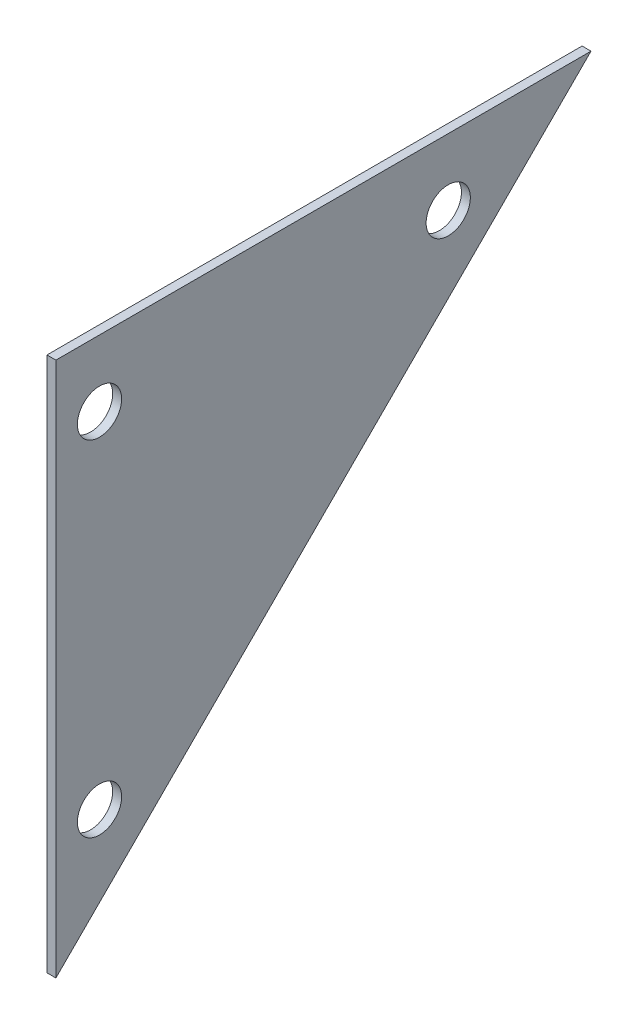
SolidWorks part; units mm, degrees
ref_plane "Front Plane" through (0, 0, 0) normal (0, 0, 1) x (1, 0, 0)
ref_plane "Top Plane" through (0, 0, 0) normal (0, 1, 0) x (1, 0, 0)
ref_plane "Right Plane" through (0, 0, 0) normal (1, 0, 0) x (0, 0, -1)
sketch "Sketch1" plane through (0, 0, 0) normal (1, 0, 0) x (0, 0, -1)
  line L0 (112.9407, 23.9242) -> (-39.4593, -128.4758)
  line L1 (-39.4593, 23.9242) -> (112.9407, 23.9242)
  line L2 (-39.4593, 23.9242) -> (-39.4593, -128.4758)
  dimension "D1" = 152.4
  dimension "D2" = 152.4
extrude "Boss-Extrude1" add sketch "Sketch1" along normal blind 2.54
sketch "Sketch2" plane through (2.54, 0, 0) normal (1, 0, 0) x (0, 0, -1)
  circle A0 centre (-27.0399, -93.1123) radius 9.525
  circle A1 centre (-27.0399, 5.0075) radius 9.525
  circle A2 centre (72.2765, 5.0075) radius 9.525
hole_wizard "CSK for M6 Flat Head Machine Screw1" positions "3DSketch1" profile "Sketch3" countersink size "M6" standard "ANSI Metric" end condition through all
sketch3d "3DSketch1"
  point P0 (2.54, 5.0075, 27.0399)
  point P3 (2.54, 5.0075, -72.2765)
  point P6 (2.54, -93.1123, 27.0399)
sketch "Sketch3" plane through (2.54, 5.0075, 27.0399) normal (0, 1, 0) x (0, 0, -1)
  line L0 (0, 0) -> (0, 2.54)
  line L1 (0, 2.54) -> (3.3, 2.54)
  line L2 (3.3, 2.54) -> (3.3, 28.4)
  line L3 (3.3, 28.4) -> (6.3, 25.4)
  line L4 (6.3, 25.4) -> (6.3, 0)
  line L6 (6.3, 0) -> (0, 0)
  line L7 (-3.3, 28.4) -> (-6.3, 25.4) construction
  line L11 (0, -6.35) -> (0, 107.95) construction
  dimension "Thru Hole Dia." = 6.6
  dimension "Thru Hole Depth" = 2.54
  dimension "C'Sink Dia." = 12.6
  dimension "C'Sink Angle" = 90
  dimension "Head Clearance" = 25.4
